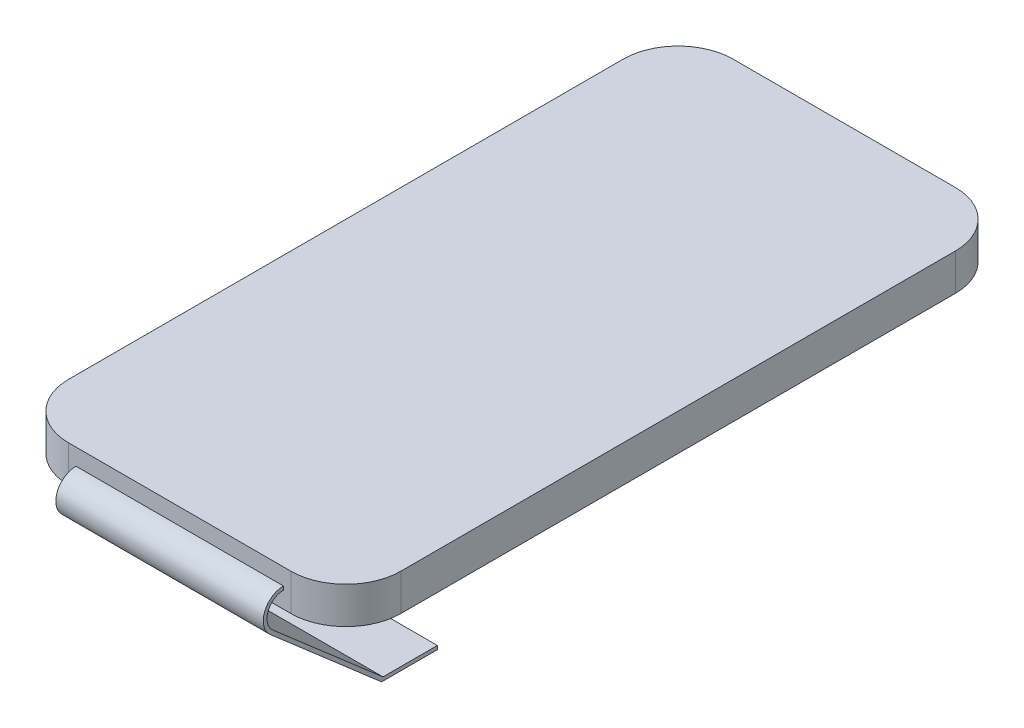
SolidWorks part; units mm, degrees
ref_plane "前视基准面" through (0, 0, 0) normal (0, 0, 1) x (1, 0, 0)
ref_plane "上视基准面" through (0, 0, 0) normal (0, 1, 0) x (1, 0, 0)
ref_plane "右视基准面" through (0, 0, 0) normal (1, 0, 0) x (0, 0, -1)
other "Configuration Table"
sketch "草图1" plane through (0, 0, 0) normal (0, 1, 0) x (1, 0, 0)
  line L0 (86.9313, 440.6974) -> (486.9313, 440.6974) construction
  line L1 (-9.05, -18.1) -> (9.05, -18.1)
  line L2 (-9.05, -18.1) -> (-9.05, 18.1)
  line L3 (-9.05, 18.1) -> (9.05, 18.1)
  line L4 (9.05, -18.1) -> (9.05, 18.1)
  line L5 (0, 18.1) -> (0, -18.1) construction
  line L6 (-9.05, 0) -> (9.05, 0) construction
  point P0 (0, 0)
  dimension "D1" = 18.1
  dimension "D2" = 36.2
extrude "凸台-拉伸1" add sketch "草图1" along normal blind 2
fillet "圆角1" radius 3 4 edges at (-9.05, 1, 18.1) (-9.05, 1, -18.1) (9.05, 1, -18.1) (9.05, 1, 18.1)
sketch "草图2" plane through (0, 0, 0) normal (1, 0, 0) x (0, 0, -1)
  line L0 (-18.1, 0) -> (-18.1, 2) construction
  line L1 (-18.7556, -0.7551) -> (-12.7148, -6) construction
  line L2 (-12.7148, -6) -> (-9.7148, -6) construction
  line L3 (-15.1, 0) -> (15.1, 0) construction
  line L4 (-18.8212, -0.8306) -> (-12.7522, -6.1)
  line L5 (-12.7522, -6.1) -> (-9.7148, -6.1)
  line L6 (-18.6901, -0.6796) -> (-12.6775, -5.9)
  line L7 (-12.6775, -5.9) -> (-9.7148, -5.9)
  line L8 (-18.1, 1.1) -> (-18.1, 0.9)
  line L9 (-9.7148, -6.1) -> (-9.7148, -5.9)
  arc A0 (-18.1, 1) -> (-18.7556, -0.7551) centre (-18.1, 0) ccw construction
  arc A1 (-18.1, 1.1) -> (-18.8212, -0.8306) centre (-18.1, 0) ccw
  arc A2 (-18.1, 0.9) -> (-18.6901, -0.6796) centre (-18.1, 0) ccw
  point P9 (0, 0)
  point P10 (-18.1276, 1)
  point P11 (-11.5883, -9)
  point P12 (-13.8436, -9)
  point P15 (-13.7049, -9.1602)
  point P16 (-13.2291, -9.2791)
  dimension "D2" = 1
  dimension "D1" = 3
  dimension "D3" = 8
  dimension "D4" = 6
  dimension "D6" = 0.1
  dimension "D7" = 0.1
extrude "凸台-拉伸2" add sketch "草图2" along normal mid plane 11.3
